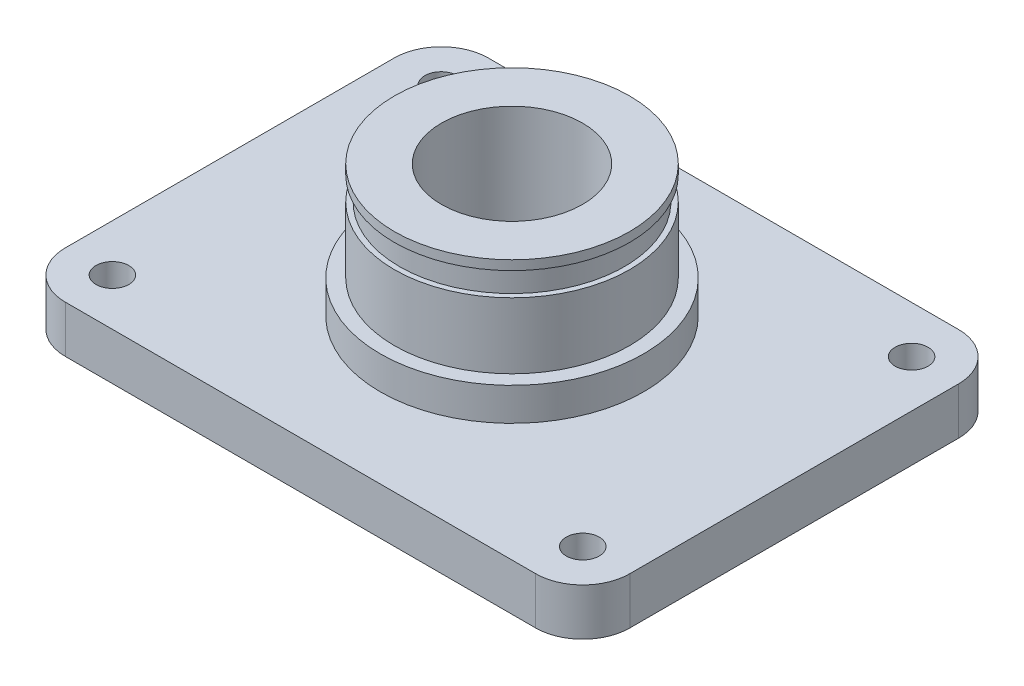
SolidWorks part; units mm, degrees
ref_plane "Front Plane" through (0, 0, 0) normal (0, 0, 1) x (1, 0, 0)
ref_plane "Top Plane" through (0, 0, 0) normal (0, 1, 0) x (1, 0, 0)
ref_plane "Right Plane" through (0, 0, 0) normal (1, 0, 0) x (0, 0, -1)
sketch "Sketch1" plane through (0, 0, 0) normal (0, 1, 0) x (1, 0, 0)
  circle A0 centre (0, 0) radius 9.5
  circle A1 centre (0, 0) radius 12.5
  dimension "D1" = 19
  dimension "D2" = 25
extrude "Boss-Extrude1" add sketch "Sketch1" along normal blind 14
sketch "Sketch2" plane through (0, 0, 0) normal (0, -1, 0) x (-1, 0, 0)
  line L1 (32.2531, 23.9169) -> (-32.2531, 23.9169)
  line L2 (32.2531, 23.9169) -> (32.2531, -23.9169)
  line L3 (32.2531, -23.9169) -> (-32.2531, -23.9169)
  line L4 (-32.2531, 23.9169) -> (-32.2531, -23.9169)
  line L5 (32.2531, 23.9169) -> (-32.2531, -23.9169) construction
  line L6 (32.2531, -23.9169) -> (-32.2531, 23.9169) construction
  point P0 (0, 0)
extrude "Boss-Extrude2" add sketch "Sketch2" along normal blind 5
sketch "Sketch3" plane through (0, 0, 0) normal (0, 1, 0) x (1, 0, 0)
  circle A0 centre (0, 0) radius 7.5
  dimension "D1" = 15
extrude "Cut-Extrude1" cut sketch "Sketch3" against normal blind 5
fillet "Fillet1" radius 10 4 edges at (-32.2531, -2.5, -23.9169) (-32.2531, -2.5, 23.9169) (32.2531, -2.5, 23.9169) (32.2531, -2.5, -23.9169)
sketch "Sketch4" plane through (0, 0, 0) normal (0, 1, 0) x (1, 0, 0)
  circle A0 centre (0, 0) radius 22.479
  circle A1 centre (0, 0) radius 41.3392
extrude "Cut-Extrude2" cut sketch "Sketch4" against normal blind 10
sketch "Sketch5" plane through (0, -5, 0) normal (0, -1, 0) x (-1, 0, 0)
  line L1 (30, 22.479) -> (-30, 22.479)
  line L2 (30, 22.479) -> (30, -22.479)
  line L3 (30, -22.479) -> (-30, -22.479)
  line L4 (-30, 22.479) -> (-30, -22.479)
  line L5 (30, 22.479) -> (-30, -22.479) construction
  line L6 (30, -22.479) -> (-30, 22.479) construction
  circle A0 centre (0, 0) radius 6
  point P0 (0, 0)
  dimension "D1" = 60
extrude "Boss-Extrude3" add sketch "Sketch5" against normal up to surface (5 mm away) up to face at (0, 0, 12.5)
fillet "Fillet2" radius 5 4 edges at (30, -2.5, -22.479) (30, -2.5, 22.479) (-30, -2.5, -22.479) (-30, -2.5, 22.479)
sketch "Sketch6" plane through (0, -5, 0) normal (0, -1, 0) x (-1, 0, 0)
  circle A0 centre (0, 0) radius 7.5
  dimension "D1" = 15
extrude "Cut-Extrude3" cut sketch "Sketch6" against normal blind 10.4357
sketch "Sketch7" plane through (0, 0, 0) normal (0, 1, 0) x (1, 0, 0)
  circle A0 centre (0, 0) radius 12.5
  circle A1 centre (0, 0) radius 14
  dimension "D1" = 28
extrude "Boss-Extrude4" add sketch "Sketch7" along normal blind 3.5
ref_plane "Plane1" through (0, 13, 0) normal (0, 1, 0) x (1, 0, 0)
sketch "Sketch8" plane through (0, 13, 0) normal (0, 1, 0) x (1, 0, 0)
  circle A0 centre (0, 0) radius 11.95
  circle A1 centre (0, 0) radius 13.1759
  dimension "D1" = 23.9
extrude "Cut-Extrude4" cut sketch "Sketch8" against normal blind 2.5
sketch "Sketch9" plane through (0, 14, 0) normal (0, 1, 0) x (1, 0, 0)
  circle A0 centre (0, 0) radius 9.5
  circle A1 centre (0, 0) radius 7.5
extrude "Boss-Extrude5" add sketch "Sketch9" against normal up to surface (14 mm away) up to face at (0, 0, 7.5)
sketch "Sketch11" plane through (0, 0, 0) normal (0, 1, 0) x (1, 0, 0)
  circle A0 centre (-25, 17.479) radius 1.75
  circle A1 centre (25, 17.479) radius 1.75
  circle A2 centre (25, -17.479) radius 1.75
  circle A3 centre (-25, -17.479) radius 1.75
  dimension "D1" = 3.5
extrude "Cut-Extrude5" cut sketch "Sketch11" against normal blind 6.2
